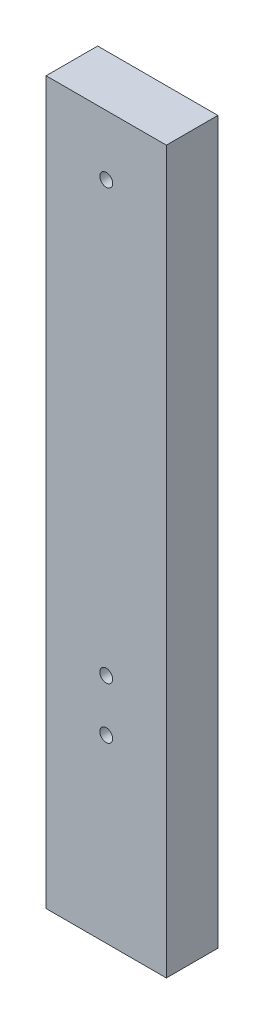
SolidWorks part; units mm, degrees
material "Oak"
ref_plane "Front" through (0, 0, 0) normal (0, 0, 1) x (1, 0, 0)
ref_plane "Top" through (0, 0, 0) normal (0, 1, 0) x (1, 0, 0)
ref_plane "Right" through (0, 0, 0) normal (1, 0, 0) x (0, 0, -1)
sketch "Sketch1" plane through (0, 0, 0) normal (0, 0, 1) x (1, 0, 0)
  line L1 (0, 0) -> (88.9, 0)
  line L2 (0, 0) -> (0, 533.4)
  line L3 (0, 533.4) -> (88.9, 533.4)
  line L4 (88.9, 0) -> (88.9, 533.4)
  dimension "D1" = 533.4
  dimension "D2" = 88.9
extrude "Boss-Extrude1" add sketch "Sketch1" along normal blind 38.1
hole_wizard "3/8 (0.375) Diameter Hole1" positions "Sketch3" profile "Sketch2" hole size "3/8" standard "ANSI Inch"
sketch "Sketch3" plane through (0, 0, 38.1) normal (0, 0, 1) x (1, 0, 0)
  line L0 (88.9, 533.4) -> (0, 533.4) construction
  line L1 (0, 533.4) -> (0, 0) construction
  point P0 (44.45, 488.95)
  dimension "D1" = 44.45
  dimension "D2" = 44.45
sketch "Sketch2" plane through (44.45, 488.95, 38.1) normal (1, 0, 0) x (0, -1, 0)
  line L0 (0, 0) -> (0, 79.0616)
  line L1 (0, 79.0616) -> (4.7625, 76.2)
  line L2 (4.7625, 76.2) -> (4.7625, 0)
  line L5 (4.7625, 0) -> (0, 0)
  line L10 (0, 79.0616) -> (-4.7625, 76.2) construction
  line L11 (0, -6.35) -> (0, 107.95) construction
  dimension "Hole Dia." = 9.525
  dimension "Hole Depth" = 76.2
  dimension "Drill Angle" = 118
sketch "Sketch4" plane through (0, 0, 38.1) normal (0, 0, 1) x (1, 0, 0)
  line L0 (0, 0) -> (88.9, 0) construction
  line L1 (88.9, 0) -> (88.9, 533.4) construction
  circle A0 centre (44.45, 133.35) radius 4.7625
  dimension "D3" = 9.525
  dimension "D1" = 133.35
  dimension "D2" = 44.45
extrude "Cut-Extrude1" cut sketch "Sketch4" against normal through all
sketch "Sketch5" plane through (0, 0, 38.1) normal (0, 0, 1) x (1, 0, 0)
  line L0 (0, 533.4) -> (0, 0) construction
  circle A0 centre (44.45, 171.45) radius 4.7625
  circle A1 centre (44.45, 133.35) radius 4.7625 construction
  dimension "D2" = 44.45
  dimension "D3" = 9.525
  dimension "D1" = 38.1
extrude "Cut-Extrude2" cut sketch "Sketch5" against normal through all
